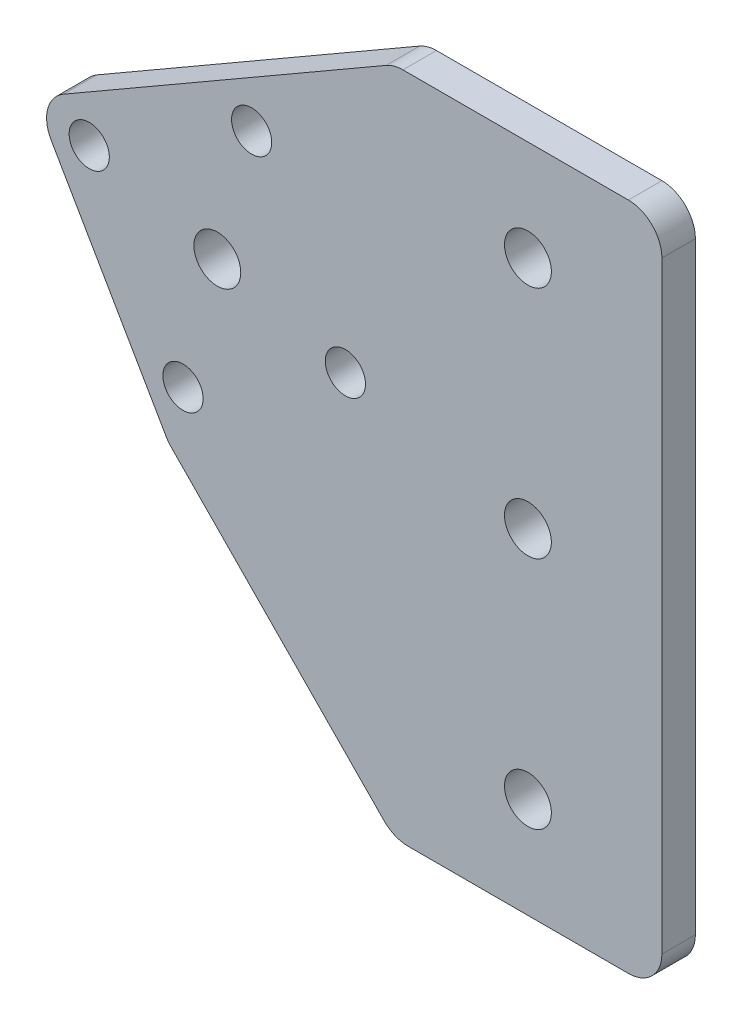
SolidWorks part; units mm, degrees
other "Objet de détail1"
other "Objet de détail2"
ref_plane "Front" through (0, 0, 0) normal (0, 0, 1) x (1, 0, 0)
ref_plane "Top" through (0, 0, 0) normal (0, 1, 0) x (1, 0, 0)
ref_plane "Right" through (0, 0, 0) normal (1, 0, 0) x (0, 0, -1)
sketch "Esquisse1" plane through (0, 0, 0) normal (0, 0, 1) x (1, 0, 0)
  line L0 (0, 0) -> (0, 100)
  line L1 (0, 100) -> (-40, 100)
  line L2 (-40, 100) -> (-93.6936, 69)
  line L3 (-93.6936, 69) -> (-73.6936, 34.359)
  line L4 (-73.6936, 34.359) -> (-40, 0)
  line L5 (-40, 0) -> (0, 0)
  line L6 (-40, 100) -> (-40, 0) construction
  point P2 (-101.4946, 55.4332)
  dimension "D1" = 40
  dimension "D2" = 60
  dimension "D3" = 62
  dimension "D4" = 100
extrude "Boss.-Extru.1" add sketch "Esquisse1" along normal blind 5
sketch "Esquisse2" plane through (0, 0, 5) normal (0, 0, 1) x (1, 0, 0)
  line L0 (-20, 100) -> (-20, 0) construction
  line L1 (0, 100) -> (-40, 100) construction
  line L2 (-40, 0) -> (0, 0) construction
  line L3 (-20, 50) -> (-1.4679, 50) construction
  line L4 (-83.6936, 51.6795) -> (-66.3731, 61.6795) construction
  line L5 (-93.6936, 69) -> (-73.6936, 34.359) construction
  line L6 (-66.3731, 61.6795) -> (-76.3731, 79) construction
  line L7 (-40, 100) -> (-93.6936, 69) construction
  circle A0 centre (-20, 15) radius 3.5
  circle A1 centre (-20, 50) radius 3.5
  circle A2 centre (-20, 85) radius 3.5
  circle A3 centre (-66.3731, 61.6795) radius 3.5
  circle A4 centre (-85.4974, 66.8038) radius 3
  circle A5 centre (-61.2487, 80.8038) radius 3
  circle A6 centre (-47.2487, 56.5551) radius 3
  circle A7 centre (-71.4974, 42.5551) radius 3
  dimension "D1" = 35
  dimension "D2" = 7
  dimension "D4" = 6
  dimension "D5" = 28
  dimension "D6" = 28
  dimension "D3" = 20
extrude "Enlèv. mat.-Extru.1" cut sketch "Esquisse2" against normal through all both and the other way through all
fillet "Congé1" radius 5 6 edges at (-40, 100, 2.5) (0, 100, 2.5) (0, 0, 2.5) (-40, 0, 2.5) (-73.6936, 34.359, 2.5) (-93.6936, 69, 2.5)
